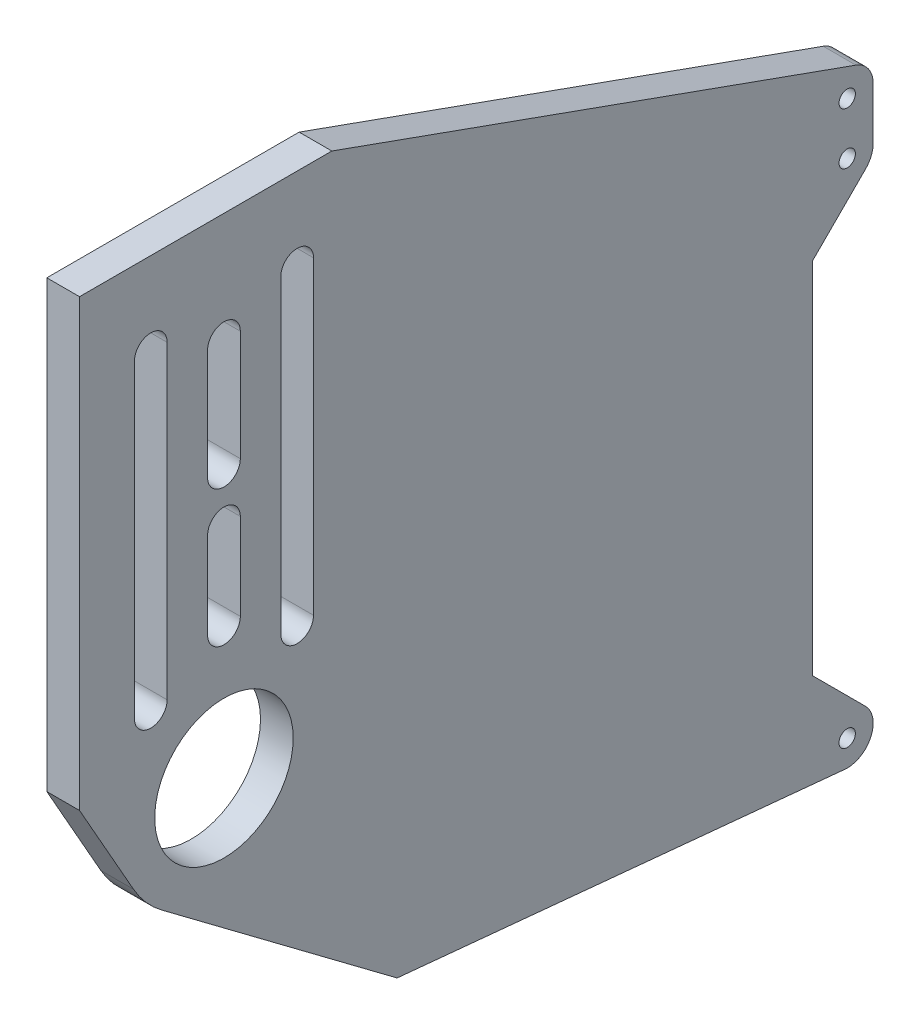
SolidWorks part; units mm, degrees
ref_plane "Front Plane" through (0, 0, 0) normal (0, 0, 1) x (1, 0, 0)
ref_plane "Top Plane" through (0, 0, 0) normal (0, 1, 0) x (1, 0, 0)
ref_plane "Right Plane" through (0, 0, 0) normal (1, 0, 0) x (0, 0, -1)
sketch "PlateGeometry" plane through (0, 0, 0) normal (1, 0, 0) x (0, 0, -1)
  line L1 (-38.1, -76.2) -> (38.1, -76.2) construction
  line L2 (-38.1, -76.2) -> (-38.1, 76.2) construction
  line L3 (-38.1, 76.2) -> (38.1, 76.2) construction
  line L4 (38.1, -76.2) -> (38.1, 76.2) construction
  line L5 (-38.1, -76.2) -> (38.1, 76.2) construction
  line L6 (-38.1, 76.2) -> (38.1, -76.2) construction
  line L11 (31.75, 76.2) -> (-31.75, 76.2) construction
  line L12 (31.75, 76.2) -> (31.75, -76.2) construction
  line L13 (31.75, -76.2) -> (-31.75, -76.2) construction
  line L14 (-31.75, 76.2) -> (-31.75, -76.2) construction
  line L15 (31.75, 76.2) -> (-31.75, -76.2) construction
  line L16 (31.75, -76.2) -> (-31.75, 76.2) construction
  point P0 (0, 0)
  point P6 (-44.4481, -57.148)
  point P7 (0, 0)
  point P8 (-43.0025, -57.15)
  point P9 (0, 0)
  point P14 (0, 0)
  point P15 (-43.2919, -50.698)
  line B0 (-35.7923, -66.6761) -> (-32.7923, -66.6739)
  line B1 (-35.7923, -66.6761) -> (-35.7877, -73.0261)
  line B2 (-35.7877, -73.0261) -> (-32.7877, -73.0239)
  line B3 (-32.7923, -66.6739) -> (-32.7877, -73.0239)
  line B4 (-35.7923, -66.6761) -> (-32.7877, -73.0239) construction
  line B5 (-35.7877, -73.0261) -> (-32.7923, -66.6739) construction
  line B6 (-35.7923, -53.9761) -> (-35.7877, -60.3261)
  line B7 (-35.7877, -60.3261) -> (-32.7877, -60.3239)
  line B8 (-35.7877, -60.3261) -> (-32.7923, -53.9739) construction
  line B9 (-35.7923, -41.2761) -> (-32.7923, -41.2739)
  line B10 (-35.7923, -41.2761) -> (-35.7877, -47.6261)
  line B11 (-35.7877, -47.6261) -> (-32.7877, -47.6239)
  line B12 (-32.7923, -41.2739) -> (-32.7877, -47.6239)
  line B13 (-35.7923, -41.2761) -> (-32.7877, -47.6239) construction
  line B14 (-35.7877, -47.6261) -> (-32.7923, -41.2739) construction
  line B15 (-35.7877, -34.9261) -> (-32.7877, -34.9239)
  line B16 (-32.7923, -28.5739) -> (-32.7877, -34.9239)
  line B17 (-35.7923, -15.8761) -> (-35.7877, -22.2261)
  line B18 (-32.7923, -15.8739) -> (-32.7877, -22.2239)
  line B19 (-35.7923, 9.5239) -> (-32.7923, 9.5261)
  line B20 (-32.7923, 9.5261) -> (-32.7877, 3.1761)
  line B21 (-35.7923, 9.5239) -> (-32.7877, 3.1761) construction
  line B22 (-35.7923, 22.2239) -> (-35.7877, 15.8739)
  line B23 (-35.7923, 34.9239) -> (-35.7877, 28.5739)
  line B24 (-35.7923, 47.6239) -> (-35.7877, 41.2739)
  line B25 (-35.7877, 41.2739) -> (-32.7923, 47.6261) construction
  line B26 (32.7886, -66.6757) -> (32.7914, -73.0257)
  line B27 (32.7914, -73.0257) -> (35.7914, -73.0243)
  line B28 (35.7886, -66.6743) -> (35.7914, -73.0243)
  line B29 (32.7886, -66.6757) -> (35.7914, -73.0243) construction
  line B30 (32.7914, -73.0257) -> (35.7886, -66.6743) construction
  line B31 (35.7886, -41.2743) -> (35.7914, -47.6243)
  line B32 (32.7886, -28.5757) -> (35.7914, -34.9243) construction
  line B33 (32.7886, -15.8757) -> (32.7914, -22.2257)
  line B34 (32.7886, -3.1757) -> (35.7914, -9.5243) construction
  line B35 (32.7914, -9.5257) -> (35.7886, -3.1743) construction
  line B36 (32.7886, 9.5243) -> (35.7886, 9.5257)
  line B37 (32.7886, 9.5243) -> (32.7914, 3.1743)
  line B38 (32.7914, 3.1743) -> (35.7914, 3.1757)
  line B39 (32.7886, 9.5243) -> (35.7914, 3.1757) construction
  line B40 (32.7886, 22.2243) -> (32.7914, 15.8743)
  line B41 (35.7886, 22.2257) -> (35.7914, 15.8757)
  line B42 (32.7886, 22.2243) -> (35.7914, 15.8757) construction
  line B43 (32.7914, 15.8743) -> (35.7886, 22.2257) construction
  line B44 (32.7914, 41.2743) -> (35.7914, 41.2757)
  line B45 (35.7886, 47.6257) -> (35.7914, 41.2757)
  line B46 (32.7886, 60.3243) -> (32.7914, 53.9743)
  line B47 (35.7886, 60.3257) -> (35.7914, 53.9757)
  line B48 (32.7886, 73.0243) -> (32.7914, 66.6743)
  line B49 (35.7886, 73.0257) -> (35.7914, 66.6757)
  line B50 (32.7914, 66.6743) -> (35.7886, 73.0257) construction
  circle B51 centre (-37.3063, -73.025) radius 5.5563 construction
  circle B52 centre (-37.3063, -73.025) radius 6.8263 construction
  circle B53 centre (-44.9262, -53.975) radius 5.5563 construction
  circle B54 centre (-44.9262, -53.975) radius 6.8263 construction
  dimension "D11" = 63.5
  dimension "D12" = 3.175
  dimension "D1" = 76.2
  dimension "D2" = 152.4
  dimension "D4" = 3.81
  dimension "D5" = 6.35
  dimension "D6" = 12.7
  dimension "D7" = 6.35
  dimension "D8" = 3.81
  dimension "D10" = 12.7
  dimension "D13" = 19.05
  dimension "D14" = 7.62
  dimension "D3" = 12
  dimension "D9" = 12
sketch_block_instance "SlotOutline-1"
sketch_block "SlotOutline" parameters "D1"=18.06, "D2"=7.2935
sketch_block_instance "SlotOutline-2"
sketch_block_instance "SlotOutline-3"
sketch_block_instance "SlotOutline-4"
sketch_block_instance "SlotOutline-5"
sketch_block_instance "SlotOutline-6"
sketch_block_instance "SlotOutline-7"
sketch_block_instance "SlotOutline-8"
sketch_block_instance "SlotOutline-9"
sketch_block_instance "SlotOutline-10"
sketch_block_instance "SlotOutline-11"
sketch_block_instance "SlotOutline-12"
sketch_block_instance "SlotOutline-13"
sketch_block_instance "SlotOutline-14"
sketch_block_instance "SlotOutline-15"
sketch_block_instance "SlotOutline-16"
sketch_block_instance "SlotOutline-17"
sketch_block_instance "SlotOutline-18"
sketch_block_instance "SlotOutline-19"
sketch_block_instance "SlotOutline-20"
sketch_block_instance "SlotOutline-21"
sketch_block_instance "SlotOutline-22"
sketch_block_instance "SlotOutline-23"
sketch_block_instance "SlotOutline-24"
sketch_block_instance "PulleyOutline-1"
sketch_block "PulleyOutline" parameters "D1"=11.1125, "D2"=13.6525
sketch_block_instance "PulleyOutline-2"
sketch "MotorGeometry" plane through (0, 0, 0) normal (1, 0, 0) x (0, 0, -1)
  line L0 (-83.2734, 1.775) -> (-83.2734, 49.025) construction
  line L3 (-50.2786, -55.4665) -> (-63.8121, -13.9087) construction
  line L4 (-41.2645, -76.9242) -> (-75.3216, -19.0975) construction
  line L5 (-38.1, -76.2) -> (-38.1, 76.2) construction
  line L6 (-38.1, -76.2) -> (38.1, -76.2) construction
  line L7 (38.1, -76.2) -> (38.1, 76.2) construction
  line L8 (-83.2734, 17.65) -> (-69.85, 9.9) construction
  line L9 (-69.85, 9.9) -> (-56.4266, 17.65) construction
  line L10 (-56.4266, 17.65) -> (-56.4266, 33.15) construction
  line L11 (-56.4266, 33.15) -> (-69.85, 40.9) construction
  line L12 (-69.85, 40.9) -> (-83.2734, 33.15) construction
  line L13 (-83.2734, 33.15) -> (-83.2734, 17.65) construction
  line L14 (-86.2734, 1.775) -> (-86.2734, 49.025)
  line L15 (-80.2734, 1.775) -> (-80.2734, 49.025)
  line L16 (-56.4266, 1.775) -> (-56.4266, 49.025) construction
  line L17 (-59.4266, 1.775) -> (-59.4266, 49.025)
  line L18 (-53.4266, 1.775) -> (-53.4266, 49.025)
  line L19 (-69.85, 8.3125) -> (-69.85, 47.25) construction
  line L20 (-72.85, 8.3125) -> (-72.85, 47.25)
  line L21 (-66.85, 8.3125) -> (-66.85, 47.25)
  circle A0 centre (44.45, -66.675) radius 1.5
  circle A1 centre (-69.85, -15.875) radius 11
  circle A5 centre (-69.85, -15.875) radius 30 construction
  circle A6 centre (-69.85, -15.875) radius 6.35 construction
  circle A7 centre (-44.9262, -53.975) radius 5.5562 construction
  circle A8 centre (-37.3063, -73.025) radius 5.5562 construction
  circle A9 centre (-69.85, -15.875) radius 25.5 construction
  circle A10 centre (-69.85, 25.4) radius 16 construction
  circle A11 centre (-69.85, 25.4) radius 11.5 construction
  circle A12 centre (-69.85, 25.4) radius 13.4234 construction
  arc A13 (-86.2734, 1.775) -> (-80.2734, 1.775) centre (-83.2734, 1.775) ccw
  arc A14 (-80.2734, 49.025) -> (-86.2734, 49.025) centre (-83.2734, 49.025) ccw
  arc A15 (-59.4266, 1.775) -> (-53.4266, 1.775) centre (-56.4266, 1.775) ccw
  arc A16 (-53.4266, 49.025) -> (-59.4266, 49.025) centre (-56.4266, 49.025) ccw
  arc A17 (-72.85, 8.3125) -> (-66.85, 8.3125) centre (-69.85, 8.3125) ccw
  arc A18 (-66.85, 47.25) -> (-72.85, 47.25) centre (-69.85, 47.25) ccw
  point P29 (-83.2734, 25.4)
  point P39 (-56.4266, 25.4)
  point P46 (-69.85, 27.7812)
  point P53 (0, 0)
  point P54 (-69.0453, 62.6709)
  point P55 (-72.3423, 70.6592)
  point P56 (-91.0269, 57.7021)
  point P57 (-67.8058, 4.4674)
  point P58 (0, 0)
  point P59 (-67.9361, 53.3841)
  point P60 (-54.0848, 47.9594)
  point P61 (-67.4577, 48.0424)
  point P62 (0, 0)
  point P63 (-71.6024, 27.9667)
  dimension "D1" = 22
  dimension "D4" = 60
  dimension "D5" = 12.7
  dimension "D7" = 4.5
  dimension "D8" = 32
  dimension "D9" = 4.5
  dimension "D13" = 3
  dimension "D3" = 6
  dimension "D2" = 31
  dimension "D6" = 38.1
  dimension "D10" = 31.75
  dimension "D11" = 9.525
  dimension "D12" = 6.35
  dimension "D14" = 15.875
  dimension "D15" = 1.5875
  dimension "D16" = 15.875
  dimension "D17" = 6.35
  dimension "D18" = 41.275
sketch "Sketch4" plane through (0, 0, 0) normal (1, 0, 0) x (0, 0, -1)
  line L0 (49.2125, 25.4) -> (49.2125, 34.925)
  line L1 (47.8176, 22.0324) -> (38.1, 12.3148)
  line L2 (-30.48, -50.8) -> (-38.1, -50.8) construction
  line L3 (-30.48, -50.8) -> (-30.48, -63.5) construction
  line L4 (-30.48, -63.5) -> (-38.1, -63.5) construction
  line L5 (-38.1, -50.8) -> (-38.1, -63.5) construction
  line L6 (-30.48, -50.8) -> (-38.1, -63.5) construction
  line L7 (-30.48, -63.5) -> (-38.1, -50.8) construction
  line L8 (38.1, 12.3148) -> (38.1, -53.5898)
  line L9 (38.1, -53.5898) -> (47.8176, -63.3074)
  line L10 (38.1, -76.2) -> (38.1, 76.2) construction
  line L11 (43.9929, -71.4155) -> (-38.1, -63.5)
  line L12 (-38.1, -63.5) -> (-81.28, -31.115)
  line L13 (-86.4236, -25.2674) -> (-96.3371, -7.7743)
  line L14 (-96.3371, -7.7743) -> (-96.3371, 73.8296)
  line L15 (-50.0636, 73.8296) -> (46.0556, 39.4087)
  line L16 (-96.3371, 73.8296) -> (-50.0636, 73.8296)
  line L17 (-83.2734, 1.775) -> (-83.2734, 58.55) construction
  line L18 (-86.2734, 1.775) -> (-86.2734, 58.55)
  line L19 (-80.2734, 1.775) -> (-80.2734, 58.55)
  line L20 (-69.85, 8.3125) -> (-69.85, 53.6) construction
  line L21 (-72.85, 8.3125) -> (-72.85, 53.6)
  line L22 (-66.85, 8.3125) -> (-66.85, 53.6)
  line L23 (-56.4266, 1.775) -> (-56.4266, 58.55) construction
  line L24 (-59.4266, 1.775) -> (-59.4266, 58.55)
  line L25 (-53.4266, 1.775) -> (-53.4266, 58.55)
  circle A0 centre (44.45, 25.4) radius 1.5
  circle A1 centre (44.45, 34.925) radius 1.5
  circle A2 centre (44.45, -66.675) radius 4.7625 construction
  circle A3 centre (44.45, 25.4) radius 4.7625 construction
  circle A4 centre (44.45, 34.925) radius 4.7625 construction
  circle A5 centre (-69.85, -15.875) radius 12.7
  arc A6 (43.9929, -71.4155) -> (47.8176, -63.3074) centre (44.45, -66.675) ccw
  circle A7 centre (-69.85, -15.875) radius 19.05
  arc A8 (47.8176, 22.0324) -> (49.2125, 25.4) centre (44.45, 25.4) ccw
  arc A9 (49.2125, 34.925) -> (46.0556, 39.4087) centre (44.45, 34.925) ccw
  circle A10 centre (44.45, -66.675) radius 1.5
  arc A11 (-86.2734, 1.775) -> (-80.2734, 1.775) centre (-83.2734, 1.775) ccw
  arc A12 (-80.2734, 58.55) -> (-86.2734, 58.55) centre (-83.2734, 58.55) ccw
  arc A13 (-72.85, 8.3125) -> (-66.85, 8.3125) centre (-69.85, 8.3125) ccw
  arc A14 (-66.85, 53.6) -> (-72.85, 53.6) centre (-69.85, 53.6) ccw
  arc A15 (-59.4266, 1.775) -> (-53.4266, 1.775) centre (-56.4266, 1.775) ccw
  arc A16 (-53.4266, 58.55) -> (-59.4266, 58.55) centre (-56.4266, 58.55) ccw
  arc A17 (-72.85, 24.1875) -> (-66.85, 24.1875) centre (-69.85, 24.1875) cw
  arc A18 (-72.85, 33.3625) -> (-66.85, 33.3625) centre (-69.85, 33.3625) ccw
  point P12 (-34.29, -57.15)
  point P36 (-83.2734, 30.1625)
  point P47 (-69.85, 30.9562)
  point P55 (-56.4266, 30.1625)
  point P71 (-50.0636, 73.8296)
  dimension "D1" = 3
  dimension "D4" = 9.525
  dimension "D9" = 25.4
  dimension "D10" = 38.1
  dimension "D11" = 6
  dimension "D14" = 3.175
  dimension "D2" = 9.525
  dimension "D3" = 101.6
  dimension "D5" = 3.81
  dimension "D6" = 12.7
  dimension "D7" = 45
  dimension "D8" = 45
  dimension "D12" = 12.7
  dimension "D13" = 25.4
  dimension "D15" = 15.875
extrude "Boss-Extrude1" add sketch "Sketch4" along normal mid plane 6
